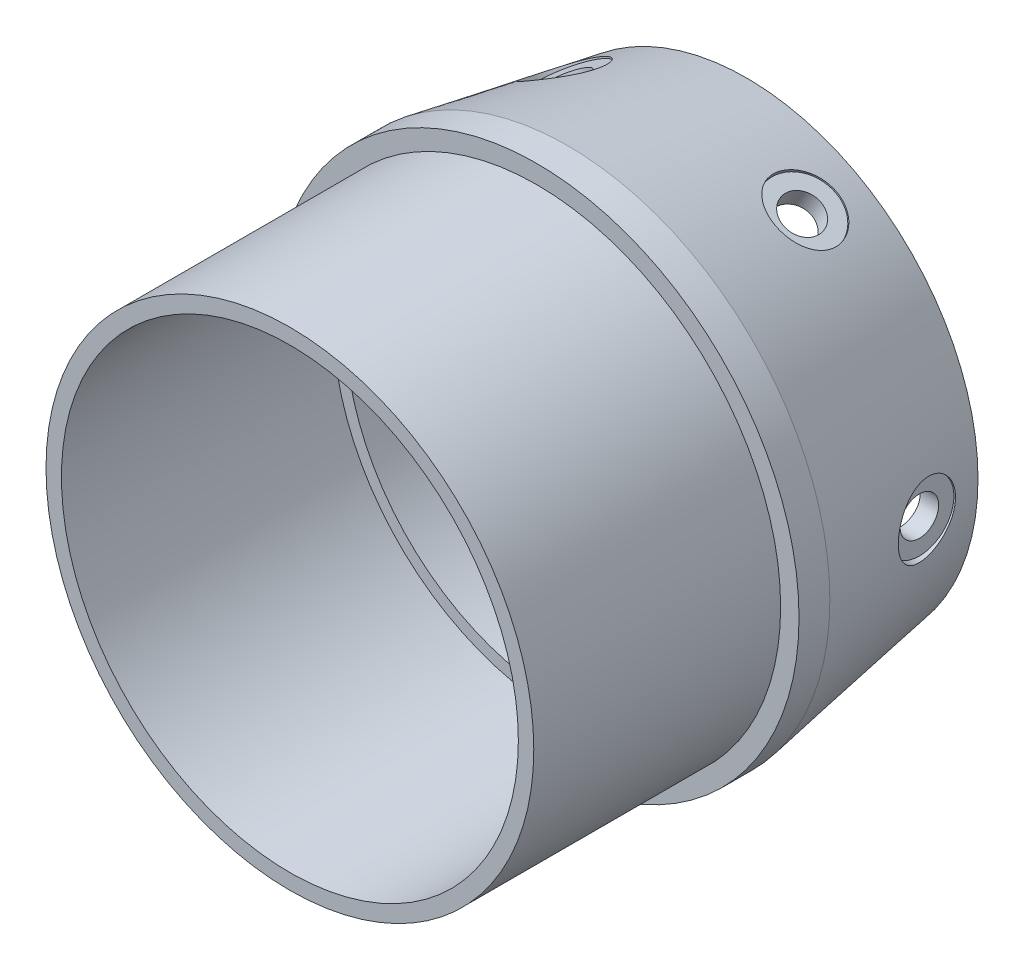
SolidWorks part; units mm, degrees
material "6061-T6 (SS)"
ref_plane "Front Plane" through (0, 0, 0) normal (0, 0, 1) x (1, 0, 0)
ref_plane "Top Plane" through (0, 0, 0) normal (0, 1, 0) x (1, 0, 0)
ref_plane "Right Plane" through (0, 0, 0) normal (1, 0, 0) x (0, 0, -1)
sketch "Sketch1" plane through (0, 0, 0) normal (1, 0, 0) x (0, 0, -1)
  line L0 (0, 0) -> (40.5624, 0) construction
  line L1 (0, 23.5077) -> (27.94, 23.5077)
  line L2 (46.99, 22.225) -> (46.99, 23.8125)
  line L5 (28.575, 26.9875) -> (25.4, 26.9875)
  line L6 (25.4, 26.9875) -> (25.4, 25.0952)
  line L7 (25.4, 25.0952) -> (0, 25.0952)
  line L8 (0, 25.0952) -> (0, 23.5077)
  line L9 (27.94, 23.5077) -> (27.94, 22.225)
  line L10 (27.94, 22.225) -> (46.99, 22.225)
  line L11 (28.575, 26.9875) -> (46.99, 23.8125)
  dimension "D1" = 50.1904
  dimension "D2" = 1.5875
  dimension "D3" = 44.45
  dimension "D4" = 25.4
  dimension "D5" = 2.54
  dimension "D6" = 53.975
  dimension "D7" = 47.625
  dimension "D8" = 19.05
  dimension "D9" = 3.175
revolve "Revolve1" add sketch "Sketch1" angle 360 about L0
sketch "Sketch2" plane through (0, 0, 0) normal (1, 0, 0) x (0, 0, -1)
  line L0 (46.99, -23.8125) -> (46.99, 23.8125) construction
  circle A0 centre (40.64, 0) radius 1.9812
  dimension "D1" = 6.35
  dimension "D2" = 3.9624
extrude "Cut-Extrude1" cut sketch "Sketch2" along normal through all
sketch "Sketch3" plane through (0, 0, 0) normal (1, 0, 0) x (0, 0, -1)
  circle A0 centre (40.64, 0) radius 3.556
  dimension "D1" = 7.112
extrude "Cut-Extrude2" cut sketch "Sketch3" along normal blind 2.54 from offset 24.13
pattern_circular "CirPattern1" count 6 over 360 about axis through (0, 0, 0) along (0, 0, 1) of "Cut-Extrude2", "Cut-Extrude1"
